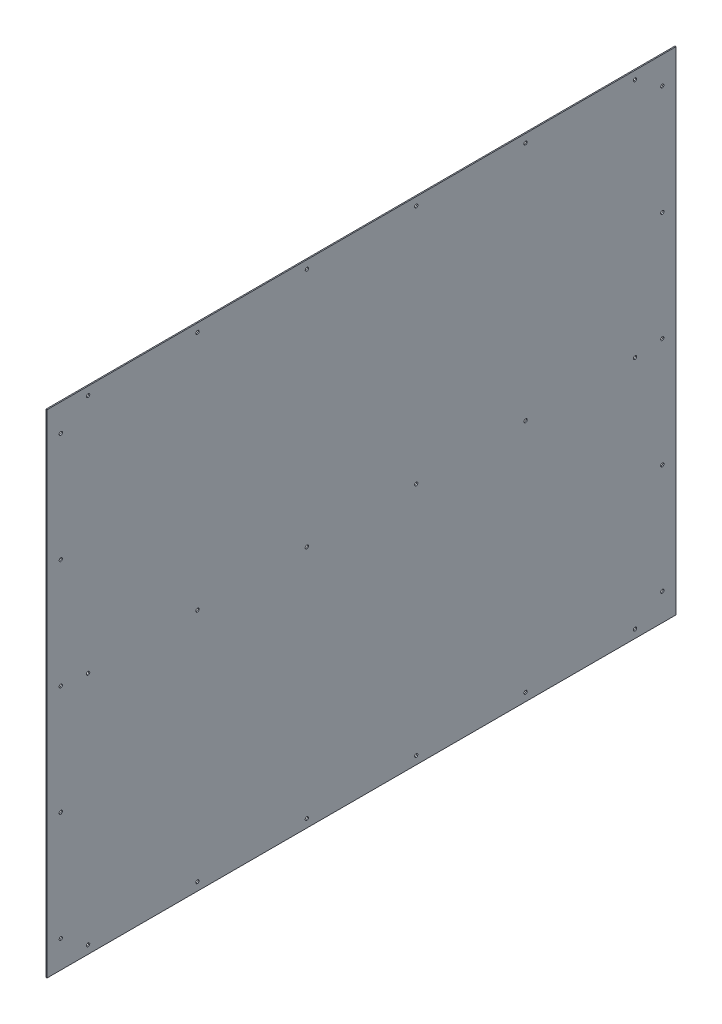
SolidWorks part; units mm, degrees
ref_plane "Front Plane" through (0, 0, 0) normal (0, 0, 1) x (1, 0, 0)
ref_plane "Top Plane" through (0, 0, 0) normal (0, 1, 0) x (1, 0, 0)
ref_plane "Right Plane" through (0, 0, 0) normal (1, 0, 0) x (0, 0, -1)
sketch "Sketch1" plane through (0, 0, 0) normal (1, 0, 0) x (0, 0, -1)
  line L1 (-575, -450) -> (575, -450)
  line L2 (-575, -450) -> (-575, 450)
  line L3 (-575, 450) -> (575, 450)
  line L4 (575, -450) -> (575, 450)
  line L5 (-575, -450) -> (575, 450) construction
  line L6 (-575, 450) -> (575, -450) construction
  point P0 (0, 0)
  dimension "D1" = 1150
  dimension "D2" = 900
extrude "Boss-Extrude1" add sketch "Sketch1" along normal blind 2
sketch "Sketch2" plane through (2, 0, 0) normal (1, 0, 0) x (0, 0, -1)
  line L0 (575, 450) -> (-575, 450) construction
  line L1 (-575, 450) -> (-575, -450) construction
  line L2 (-575, 0) -> (575, 0) construction
  line L3 (575, -450) -> (575, 450) construction
  line L4 (-575, -450) -> (575, -450) construction
  line L5 (-575, -220) -> (575, -220) construction
  circle A0 centre (-500, 435) radius 3
  circle A1 centre (-300, 435) radius 3
  circle A2 centre (-100, 435) radius 3
  circle A3 centre (100, 435) radius 3
  circle A4 centre (300, 435) radius 3
  circle A5 centre (500, 435) radius 3
  circle A6 centre (500, -435) radius 3
  circle A7 centre (300, -435) radius 3
  circle A8 centre (100, -435) radius 3
  circle A9 centre (-100, -435) radius 3
  circle A10 centre (-300, -435) radius 3
  circle A11 centre (-500, -435) radius 3
  circle A12 centre (500, -5) radius 3
  circle A13 centre (100, -5) radius 3
  circle A14 centre (300, -5) radius 3
  circle A15 centre (-100, -5) radius 3
  circle A16 centre (-300, -5) radius 3
  circle A17 centre (-500, -5) radius 3
  point P32 (-575, -220)
  point P37 (-575, -220)
  dimension "D1" = 6
  dimension "D5" = 200
  dimension "D2" = 15
  dimension "D3" = 75
  dimension "D6" = 230
  dimension "D4" = 6
extrude "Cut-Extrude1" cut sketch "Sketch2" against normal blind 2
sketch "Sketch3" plane through (2, 0, 0) normal (1, 0, 0) x (0, 0, -1)
  line L0 (-575, 450) -> (-575, -450) construction
  line L2 (575, 450) -> (-575, 450) construction
  line L3 (0, 450) -> (0, -450) construction
  line L4 (-575, -450) -> (575, -450) construction
  circle A0 centre (-550, 400) radius 3
  circle A1 centre (-550, 200) radius 3
  circle A2 centre (-550, 0) radius 3
  circle A3 centre (-550, -200) radius 3
  circle A4 centre (-550, -400) radius 3
  circle A5 centre (550, -400) radius 3
  circle A6 centre (550, -200) radius 3
  circle A7 centre (550, 0) radius 3
  circle A8 centre (550, 200) radius 3
  circle A9 centre (550, 400) radius 3
  dimension "D1" = 6
  dimension "D2" = 25
  dimension "D3" = 50
  dimension "D4" = 5
extrude "Cut-Extrude2" cut sketch "Sketch3" against normal blind 10
